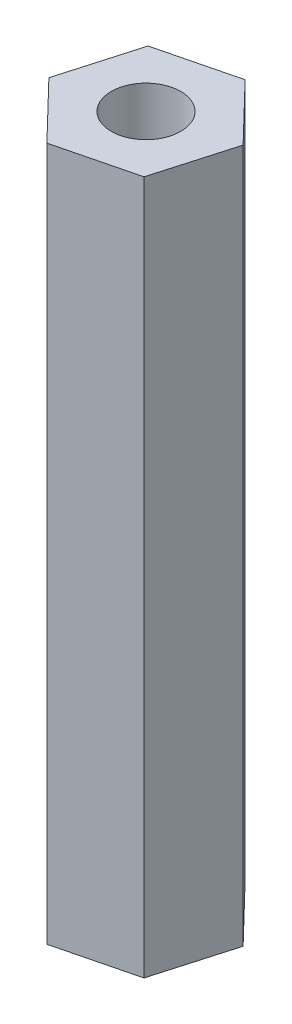
SolidWorks part; units mm, degrees
material "ABS"
ref_plane "Plano frontal" through (0, 0, 0) normal (0, 0, 1) x (1, 0, 0)
ref_plane "Plano superior" through (0, 0, 0) normal (0, 1, 0) x (1, 0, 0)
ref_plane "Plano direito" through (0, 0, 0) normal (1, 0, 0) x (0, 0, -1)
sketch "Esboço1" plane through (0, 0, 0) normal (0, 1, 0) x (1, 0, 0)
  line L1 (2.4061, -2.4921) -> (3.3613, 0.8377)
  line L2 (3.3613, 0.8377) -> (0.9551, 3.3298)
  line L3 (0.9551, 3.3298) -> (-2.4061, 2.4921)
  line L4 (-2.4061, 2.4921) -> (-3.3613, -0.8377)
  line L5 (-3.3613, -0.8377) -> (-0.9551, -3.3298)
  line L6 (-0.9551, -3.3298) -> (2.4061, -2.4921)
  circle A0 centre (0, 0) radius 3 construction
extrude "Ressalto-extrusão1" add sketch "Esboço1" along normal blind 30
sketch "Esboço2" plane through (0, 0, 0) normal (0, -1, 0) x (1, 0, 0)
  circle A0 centre (0, 0) radius 1.5
extrude "Corte-extrusão1" cut sketch "Esboço2" against normal blind 30
